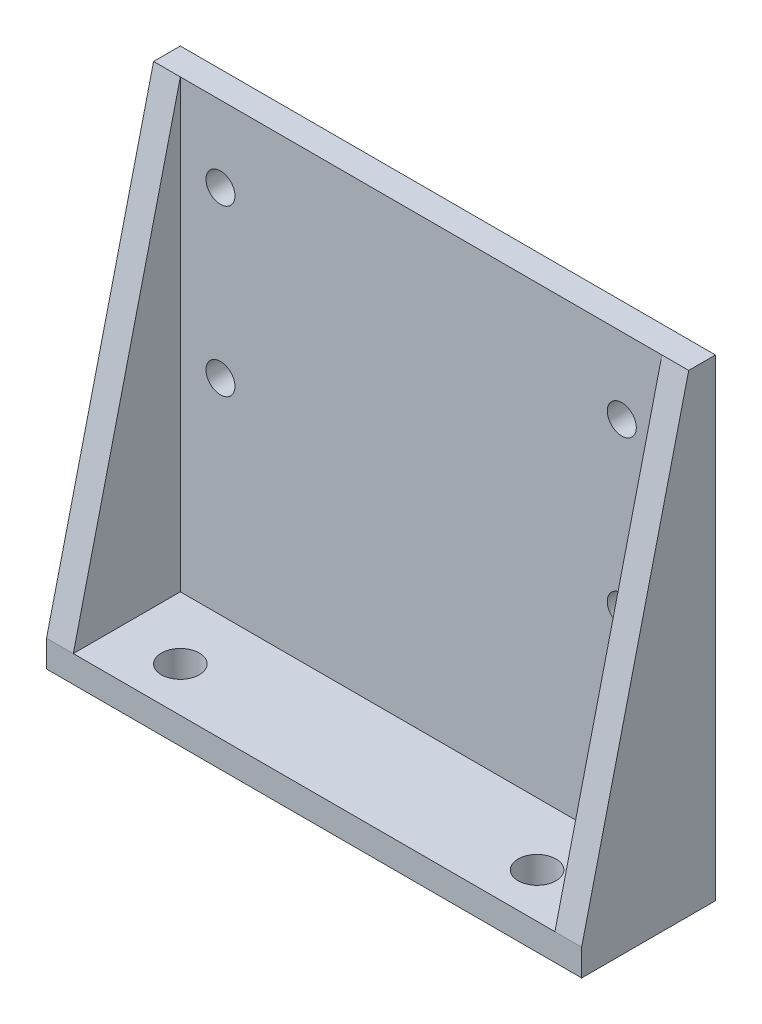
SolidWorks part; units mm, degrees
ref_plane "Front Plane" through (0, 0, 0) normal (0, 0, 1) x (1, 0, 0)
ref_plane "Top Plane" through (0, 0, 0) normal (0, 1, 0) x (1, 0, 0)
ref_plane "Right Plane" through (0, 0, 0) normal (1, 0, 0) x (0, 0, -1)
sketch "Sketch1" plane through (0, 0, 0) normal (0, 1, 0) x (1, 0, 0)
  line L0 (30, 15) -> (30, 0) construction
  line L1 (0, 0) -> (60, 0)
  line L2 (0, 0) -> (0, 15)
  line L3 (0, 15) -> (60, 15)
  line L4 (60, 0) -> (60, 15)
  circle A0 centre (10, 5) radius 2.125
  circle A1 centre (50, 5) radius 2.125
  dimension "D2" = 4.25
  dimension "D1" = 10
  dimension "D3" = 5
  dimension "D4" = 10
  dimension "D5" = 20
extrude "Boss-Extrude1" add sketch "Sketch1" along normal blind 3
sketch "Sketch2" plane through (0, 0, -15) normal (0, 0, -1) x (-1, 0, 0)
  line L0 (-30, 53) -> (-30, 3) construction
  line L1 (-60, 3) -> (0, 3)
  line L2 (-60, 3) -> (-60, 53)
  line L3 (-60, 53) -> (0, 53)
  line L4 (0, 3) -> (0, 53)
  circle A0 centre (-52.5, 44.5) radius 1.625
  circle A1 centre (-52.5, 26) radius 1.625
  circle A2 centre (-7.5, 26) radius 1.625
  circle A3 centre (-7.5, 44.5) radius 1.625
  dimension "D2" = 3.25
  dimension "D4" = 3.25
  dimension "D1" = 50
  dimension "D3" = 22.5
  dimension "D5" = 18.5
  dimension "D6" = 8.5
extrude "Boss-Extrude2" add sketch "Sketch2" against normal blind 3
sketch "Sketch3" plane through (0, 0, 0) normal (-1, 0, 0) x (0, 0, 1)
  line L0 (-12, 53) -> (0, 3)
  line L1 (0, 3) -> (-12, 3)
  line L2 (-12, 3) -> (-12, 53)
extrude "Boss-Extrude3" add sketch "Sketch3" against normal blind 3
ref_plane "Plane1" through (30, 0, 0) normal (-1, 0, 0) x (0, 0, 1)
mirror "Mirror1" about plane through (30, 0, 0) normal (-1, 0, 0) of "Boss-Extrude3"
